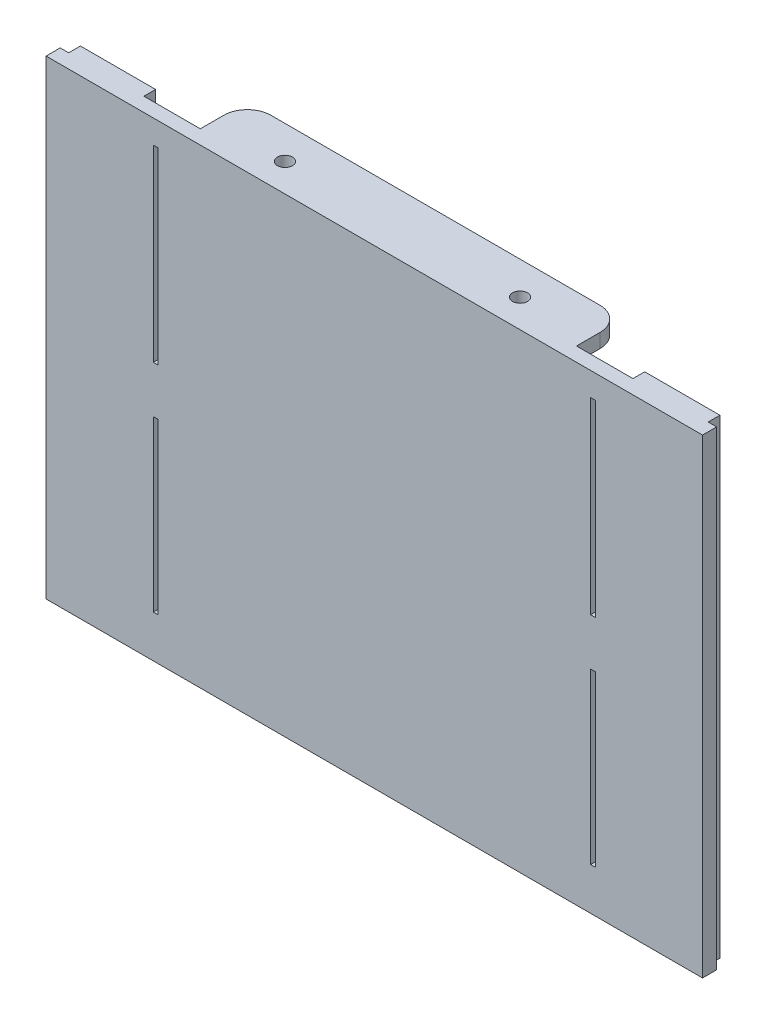
SolidWorks part; units mm, degrees
ref_plane "Front Plane" through (0, 0, 0) normal (0, 0, 1) x (1, 0, 0)
ref_plane "Top Plane" through (0, 0, 0) normal (0, 1, 0) x (1, 0, 0)
ref_plane "Right Plane" through (0, 0, 0) normal (1, 0, 0) x (0, 0, -1)
sketch "Sketch1" plane through (0, 0, 0) normal (0, 0, 1) x (1, 0, 0)
  line L1 (70, -50) -> (-70, -50)
  line L2 (70, -50) -> (70, 50)
  line L3 (70, 50) -> (-70, 50)
  line L4 (-70, -50) -> (-70, 50)
  line L5 (70, -50) -> (-70, 50) construction
  line L6 (70, 50) -> (-70, -50) construction
  point P0 (0, 0)
  dimension "D1" = 140
  dimension "D2" = 100
extrude "Boss-Extrude1" add sketch "Sketch1" along normal blind 3
sketch "Sketch2" plane through (0, 0, 0) normal (0, 0, -1) x (-1, 0, 0)
  line L0 (-60, 63.7201) -> (-60, -49936.2799) construction
  line L1 (60, 64.2305) -> (60, -49935.7695) construction
  dimension "D1" = 60
  dimension "D2" = 60
sketch "Sketch3" plane through (0, 0, 0) normal (0, 0, -1) x (-1, 0, 0)
  line L0 (-60, 200063.7201) -> (-60, -249936.2799) construction
  line L1 (-52, -50) -> (-68, -50)
  line L2 (-52, -50) -> (-52, 50)
  line L3 (-52, 50) -> (-68, 50)
  line L4 (-68, -50) -> (-68, 50)
  line L5 (-52, -50) -> (-68, 50) construction
  line L6 (-52, 50) -> (-68, -50) construction
  line L7 (-70, 50) -> (70, 50) construction
  line L8 (60, 200064.2305) -> (60, -249935.7695) construction
  line L9 (68, -50) -> (52, -50)
  line L10 (68, -50) -> (68, 50)
  line L11 (68, 50) -> (52, 50)
  line L12 (52, -50) -> (52, 50)
  line L13 (68, -50) -> (52, 50) construction
  line L14 (68, 50) -> (52, -50) construction
  point P0 (-60, 0)
  point P9 (60, 0)
  dimension "D1" = 16
  dimension "D2" = 16
extrude "Boss-Extrude2" add sketch "Sketch3" along normal blind 2.5
sketch "Sketch4" plane through (0, 0, -2.5) normal (0, 0, -1) x (-1, 0, 0)
  line L0 (-60, 200063.7201) -> (-60, -249936.2799) construction
  line L1 (-66.1, 47.75) -> (-53.9, 47.75)
  line L2 (-66.1, 47.75) -> (-66.1, 42.25)
  line L3 (-66.1, 42.25) -> (-53.9, 42.25)
  line L4 (-53.9, 47.75) -> (-53.9, 42.25)
  line L5 (-66.1, 47.75) -> (-53.9, 42.25) construction
  line L6 (-66.1, 42.25) -> (-53.9, 47.75) construction
  line L7 (-52, 50) -> (-68, 50) construction
  point P0 (-60, 45)
  dimension "D1" = 12.2
  dimension "D2" = 5
  dimension "D3" = 5.5
extrude "Cut-Extrude1" cut sketch "Sketch4" against normal blind 1.5
mirror "Mirror1" about plane through (0, 0, 0) normal (1, 0, 0) of "Cut-Extrude1"
pattern_linear "LPattern1" count 4 spacing 30 along (0, -1, 0) of "Mirror1", "Cut-Extrude1"
sketch "Sketch6" plane through (0, 50, 0) normal (0, 1, 0) x (1, 0, 0)
  line L0 (70, -3) -> (-70, -3) construction
  line L1 (-70, 0) -> (-69.8, 0)
  line L2 (-70, 0) -> (-70, -3)
  line L3 (-70, -3) -> (-69.8, -3)
  line L4 (-69.8, 0) -> (-69.8, -3)
  line L6 (70, 0) -> (69.8, 0)
  line L7 (70, 0) -> (70, -3)
  line L8 (70, -3) -> (69.8, -3)
  line L9 (69.8, 0) -> (69.8, -3)
  dimension "D1" = 0.2
  dimension "D2" = 0.2
extrude "Cut-Extrude3" cut sketch "Sketch6" against normal through all both and the other way through all
sketch "Sketch8" plane through (0, 0, 3) normal (0, 0, 1) x (1, 0, 0)
  line L0 (-60, 10.6106) -> (-60, -49989.3894) construction
  line L1 (60, 23.1735) -> (60, -49976.8265) construction
  dimension "D1" = 60
  dimension "D2" = 60
sketch "Sketch10" plane through (0, 0, 3) normal (0, 0, 1) x (1, 0, 0)
  line L0 (-66, -50) -> (-54, -50) construction
  line L1 (-60, 200010.6106) -> (-60, -249989.3894) construction
  line L2 (-69.8, -50) -> (69.8, -50) construction
  line L3 (-66, -44) -> (-54, -44)
  line L4 (-66, -56) -> (-54, -56)
  arc A0 (-66, -44) -> (-66, -56) centre (-66, -50) ccw
  arc A1 (-54, -56) -> (-54, -44) centre (-54, -50) ccw
  point P6 (-60, -50)
  dimension "D1" = 12
  dimension "D2" = 12
extrude "Cut-Extrude4" [suppressed] cut sketch "Sketch10" against normal through all both and the other way through all
mirror "Mirror3" [suppressed] about plane through (0, 0, 0) normal (1, 0, 0)
sketch "Sketch11" plane through (0, 0, -2.5) normal (0, 0, -1) x (-1, 0, 0)
  line L0 (-53.9, 12.25) -> (-60, -7.75)
  line L1 (-60, 200063.7201) -> (-60, -249936.2799) construction
  line L2 (-60, -7.75) -> (-66.1, 12.25)
  line L3 (-66.1, 12.25) -> (-53.9, 12.25)
  dimension "D1" = 20
extrude "Cut-Extrude5" cut sketch "Sketch11" against normal blind 1.5
pattern_linear "LPattern2" count 2 spacing 30 along (0, 1, 0) count 2 spacing 30 along (0, -1, 0) of "Cut-Extrude5"
mirror "Mirror4" about plane through (0, 0, 0) normal (1, 0, 0) of "LPattern2", "Cut-Extrude5"
sketch "Sketch13" plane through (0, 0, 0) normal (0, 0, -1) x (-1, 0, 0)
  line L0 (-52, -50) -> (-52, 50) construction
  line L1 (-47, 45) -> (-46, 45)
  line L2 (-47, 45) -> (-47, 5)
  line L3 (-47, 5) -> (-46, 5)
  line L4 (-46, 45) -> (-46, 5)
  line L5 (-52, -50) -> (-52, 50) construction
  line L8 (-47, -5) -> (-46, -5)
  line L9 (-47, -5) -> (-47, -41)
  line L10 (-47, -41) -> (-46, -41)
  line L11 (-46, -5) -> (-46, -41)
  dimension "D1" = 5
  dimension "D2" = 1
  dimension "D3" = 40
  dimension "D4" = 5
  dimension "D5" = 5
  dimension "D6" = 36
  dimension "D7" = 5
  dimension "D8" = 1
extrude "Cut-Extrude7" cut sketch "Sketch13" against normal blind 10
mirror "Mirror7" about plane through (0, 0, 0) normal (1, 0, 0) of "Cut-Extrude7"
sketch "Sketch15" plane through (0, 0, 0) normal (0, 0, -1) x (-1, 0, 0)
  line L0 (-52, 50) -> (52, 50) construction
  line L1 (-40, 50) -> (40, 50)
  line L2 (-40, 50) -> (-40, 47)
  line L3 (-40, 47) -> (40, 47)
  line L4 (40, 50) -> (40, 47)
  dimension "D1" = 80
  dimension "D2" = 40
  dimension "D3" = 3
extrude "Boss-Extrude4" add sketch "Sketch15" along normal blind 10
fillet "Fillet2" radius 5 2 edges at (-40, 48.5, -10) (40, 48.5, -10)
fillet "Fillet3" radius 3 1 edges at (0, 47, 0)
sketch "Sketch17" plane through (0, 0, -2.5) normal (0, 0, -1) x (-1, 0, 0)
  line L0 (-68, -50) -> (-52, -50) construction
  line L1 (-66.1, -47.75) -> (-53.9, -47.75)
  line L2 (-66.1, -47.75) -> (-66.1, -50)
  line L3 (-66.1, -50) -> (-53.9, -50)
  line L4 (-53.9, -47.75) -> (-53.9, -50)
extrude "Cut-Extrude9" cut sketch "Sketch17" against normal up to surface (1.5 mm away) up to face at (60, -45, -1)
mirror "Mirror8" about plane through (0, 0, 0) normal (1, 0, 0) of "Cut-Extrude9"
sketch "Sketch18" plane through (0, 50, 0) normal (0, 1, 0) x (1, 0, 0)
  line L0 (25, 3) -> (-25, 3) construction
  line L1 (69.8, -3) -> (-69.8, -3) construction
  circle A0 centre (-25, 3) radius 1.6
  circle A1 centre (25, 3) radius 1.6
  point P3 (0, 3)
  dimension "D3" = 3.2
  dimension "D1" = 6
  dimension "D2" = 50
extrude "Cut-Extrude10" cut sketch "Sketch18" against normal blind 10
